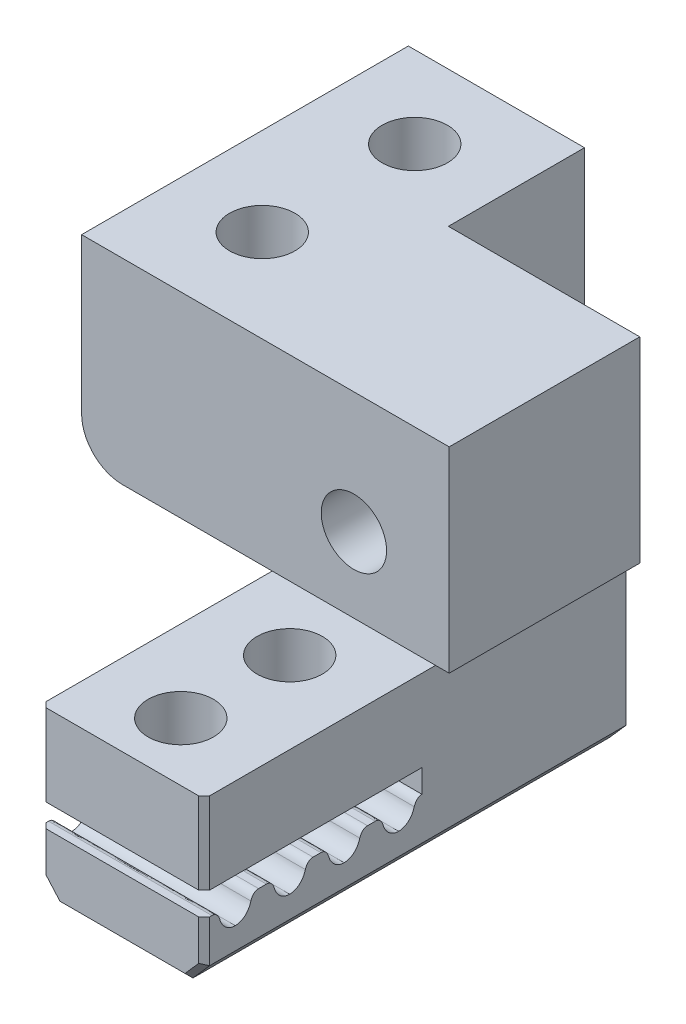
SolidWorks part; units mm, degrees
ref_plane "Front Plane" through (0, 0, 0) normal (0, 0, 1) x (1, 0, 0)
ref_plane "Top Plane" through (0, 0, 0) normal (0, 1, 0) x (1, 0, 0)
ref_plane "Right Plane" through (0, 0, 0) normal (1, 0, 0) x (0, 0, -1)
sketch "Sketch1" plane through (0, 0, 0) normal (0, 0, 1) x (1, 0, 0)
  line L0 (3, 3.05) -> (3, -2.2538)
  line L1 (-3, 3.05) -> (-3, -2.2538)
  line L7 (-3, 3.05) -> (3, 3.05)
  line L13 (-3, -2.2538) -> (-2.3882, -2.95)
  line L14 (3, -2.2538) -> (2.3882, -2.95)
  line L16 (-2.3882, -2.95) -> (2.3882, -2.95)
extrude "Boss-Extrude1" add sketch "Sketch1" along normal blind 13
sketch "Sketch6" plane through (0, 3.05, 0) normal (0, 1, 0) x (1, 0, 0)
  line L0 (-3, -5) -> (-3, 0)
  line L1 (-3, 0) -> (3, 0)
  line L3 (-3, -5) -> (3, -5)
  line L6 (3, -5) -> (3, 0)
  line L7 (3, 0) -> (-3, 0) construction
extrude "Boss-Extrude4" add sketch "Sketch6" along normal blind 5.6
sketch "Sketch16" plane through (0, 3.05, 0) normal (0, 1, 0) x (1, 0, 0)
  line L4 (3, -5) -> (-3, -5)
  line L5 (-3, -5) -> (-3, -13)
  line L6 (-3, -13) -> (3, -13)
  line L7 (3, -13) -> (3, -5)
  line L8 (3, -5) -> (-3, -5)
  line L9 (-3, -5) -> (-3, -13)
  line L10 (-3, -13) -> (3, -13)
  line L11 (3, -13) -> (3, -5)
  dimension "D1" = 0
extrude "Boss-Extrude5" add sketch "Sketch16" along normal blind 0.1
sketch "Sketch18" plane through (0, 0, 0) normal (1, 0, 0) x (0, 0, -1)
  line L0 (-8.8572, -0.0702) -> (-12.8572, -0.0702)
  line L2 (-12.8572, -0.7) -> (-12.7144, -0.7)
  line L3 (-11, -0.7) -> (-10.8572, -0.7)
  line L4 (-10.8572, -0.7) -> (-10.7144, -0.7)
  line L5 (-9, -0.7) -> (-8.8572, -0.7)
  line L6 (-8.8572, -0.7) -> (-8.7144, -0.7)
  line L7 (-7, -0.7) -> (-6.8572, -0.7)
  line L8 (-6.8572, -0.7) -> (-6.7144, -0.7)
  line L9 (-5, -0.0702) -> (-5, -0.7)
  line L11 (-5, -0.0702) -> (-8.8572, -0.0702)
  line L12 (-13, -2.95) -> (0, -2.95) construction
  line L13 (-5.8572, -1.45) -> (-5, -1.45) construction
  line L14 (-5, -1.45) -> (-11.8572, -1.45) construction
  line L15 (-5, 3.15) -> (-5, -1.45) construction
  line L16 (-5, -0.7) -> (-5, -1.45) construction
  line L17 (-12.8572, -0.0702) -> (-13, -0.0702)
  line L20 (-13, -0.0702) -> (-13, -0.7)
  line L22 (-12.8572, -0.7) -> (-13, -0.7)
  spline S0 degree 2 poles (-12.7144, -0.7) (-12.5198, -0.7) (-12.43, -0.9509) knots 0.103448 0.103448 0.103448 0.137931 0.137931 0.137931
  spline S1 degree 3 poles (-12.43, -0.9509) (-12.3594, -1.2388) (-12.13, -1.45) (-11.8572, -1.45) knots 0.137931 0.137931 0.137931 0.137931 0.172414 0.172414 0.172414 0.172414
  spline S2 degree 3 poles (-11.8572, -1.45) (-11.5844, -1.45) (-11.355, -1.2388) (-11.2844, -0.9509) knots 0.172414 0.172414 0.172414 0.172414 0.206897 0.206897 0.206897 0.206897
  spline S3 degree 2 poles (-11.2844, -0.9509) (-11.1946, -0.7) (-11, -0.7) knots 0.206897 0.206897 0.206897 0.241379 0.241379 0.241379
  spline S4 degree 2 poles (-10.7144, -0.7) (-10.5198, -0.7) (-10.43, -0.9509) knots 0.310345 0.310345 0.310345 0.344828 0.344828 0.344828
  spline S5 degree 3 poles (-10.43, -0.9509) (-10.3594, -1.2388) (-10.13, -1.45) (-9.8572, -1.45) knots 0.344828 0.344828 0.344828 0.344828 0.37931 0.37931 0.37931 0.37931
  spline S6 degree 3 poles (-9.8572, -1.45) (-9.5844, -1.45) (-9.355, -1.2388) (-9.2844, -0.9509) knots 0.37931 0.37931 0.37931 0.37931 0.413793 0.413793 0.413793 0.413793
  spline S7 degree 2 poles (-9.2844, -0.9509) (-9.1946, -0.7) (-9, -0.7) knots 0.413793 0.413793 0.413793 0.448276 0.448276 0.448276
  spline S8 degree 2 poles (-8.7144, -0.7) (-8.5198, -0.7) (-8.43, -0.9509) knots 0.517241 0.517241 0.517241 0.551724 0.551724 0.551724
  spline S9 degree 3 poles (-8.43, -0.9509) (-8.3594, -1.2388) (-8.13, -1.45) (-7.8572, -1.45) knots 0.551724 0.551724 0.551724 0.551724 0.586207 0.586207 0.586207 0.586207
  spline S10 degree 3 poles (-7.8572, -1.45) (-7.5844, -1.45) (-7.355, -1.2388) (-7.2844, -0.9509) knots 0.586207 0.586207 0.586207 0.586207 0.62069 0.62069 0.62069 0.62069
  spline S11 degree 2 poles (-7.2844, -0.9509) (-7.1946, -0.7) (-7, -0.7) knots 0.62069 0.62069 0.62069 0.655172 0.655172 0.655172
  spline S12 degree 2 poles (-6.7144, -0.7) (-6.5198, -0.7) (-6.43, -0.9509) knots 0.724138 0.724138 0.724138 0.758621 0.758621 0.758621
  spline S13 degree 3 poles (-6.43, -0.9509) (-6.3594, -1.2388) (-6.13, -1.45) (-5.8572, -1.45) knots 0.758621 0.758621 0.758621 0.758621 0.793103 0.793103 0.793103 0.793103
  spline S14 degree 3 poles (-5.8572, -1.45) (-5.5844, -1.45) (-5.355, -1.2388) (-5.2844, -0.9509) knots 0.793103 0.793103 0.793103 0.793103 0.827586 0.827586 0.827586 0.827586
  spline S15 degree 2 poles (-5.2844, -0.9509) (-5.1946, -0.7) (-5, -0.7) knots 0.827586 0.827586 0.827586 0.862069 0.862069 0.862069
  dimension "D1" = 1.5
  dimension "D2" = 1.3798
extrude "Cut-Extrude6" cut sketch "Sketch18" against normal blind 3.6 and the other way blind 4
sketch "Sketch15" plane through (0, 8.65, 0) normal (0, 1, 0) x (1, 0, 0)
  line L0 (0, -13) -> (0, -5) construction
  line L1 (-3, -13) -> (3, -13) construction
  line L2 (-3, -5) -> (3, -5) construction
  line L3 (2.008, -10.7144) -> (2.008, -11) construction
  line L4 (3, -10.7144) -> (-3, -10.7144) construction
  line L5 (3, -11) -> (-3, -11) construction
  line L6 (2.008, -10.8572) -> (0, -10.8572) construction
  line L7 (1.0382, -6.7144) -> (1.0382, -7) construction
  line L8 (3, -6.7144) -> (-3, -6.7144) construction
  line L9 (3, -7) -> (-3, -7) construction
  line L10 (1.0382, -6.8572) -> (0, -6.8572) construction
  circle A0 centre (0, -6.8572) radius 1.5 construction
  circle A1 centre (0, -10.8572) radius 1.5 construction
  circle A2 centre (0, -10.8572) radius 1.2
  circle A4 centre (0, -6.8572) radius 1.2
extrude "Cut-Extrude7" cut sketch "Sketch15" against normal up to surface (8.7202 mm away) up to face at (0, -0.0702, 9)
sketch "Sketch19" plane through (0, -0.0702, 0) normal (0, -1, 0) x (1, 0, 0)
  line L4 (-3, 13) -> (-3, 5)
  line L5 (-3, 5) -> (3, 5)
  line L6 (3, 5) -> (3, 13)
  line L7 (3, 13) -> (-3, 13)
  line L8 (-3, 13) -> (-3, 5)
  line L9 (-3, 5) -> (3, 5)
  line L10 (3, 5) -> (3, 13)
  line L11 (3, 13) -> (-3, 13)
  circle A0 centre (0, 10.8572) radius 1.2 construction
  circle A1 centre (0, 6.8572) radius 1.2 construction
  circle A2 centre (0, 10.8572) radius 1.2
  circle A3 centre (0, 6.8572) radius 1.2
  dimension "D1" = 0
extrude "Cut-Extrude8" cut sketch "Sketch19" against normal blind 0.2202
sketch "Sketch12" plane through (0, 0, 5) normal (0, 0, 1) x (1, 0, 0)
  circle A0 centre (0, 5.85) radius 1.5 construction
  circle A1 centre (0, 5.85) radius 1.2
extrude "Cut-Extrude5" cut sketch "Sketch12" against normal blind 6
sketch "Sketch21" plane through (0, 0, 0) normal (0, 0, -1) x (-1, 0, 0)
  line L10 (-2.3882, -2.95) -> (2.3882, -2.95)
  line L11 (2.3882, -2.95) -> (3, -2.2538)
  line L12 (3, -2.2538) -> (3, 8.65)
  line L13 (3, 8.65) -> (-3, 8.65)
  line L14 (-3, 8.65) -> (-3, -2.2538)
  line L15 (-3, -2.2538) -> (-2.3882, -2.95)
  line L19 (-2.3882, -2.95) -> (2.3882, -2.95)
  line L20 (2.3882, -2.95) -> (3, -2.2538)
  line L21 (3, -2.2538) -> (3, 8.65)
  line L22 (3, 8.65) -> (-3, 8.65)
  line L23 (-3, 8.65) -> (-3, -2.2538)
  line L24 (-3, -2.2538) -> (-2.3882, -2.95)
  circle A0 centre (0, 5.85) radius 1.2 construction
  circle A1 centre (0, 5.85) radius 1.2
  dimension "D1" = 0
extrude "Boss-Extrude6" add sketch "Sketch21" along normal blind 2.5
sketch "Sketch24" plane through (0, 0, 5) normal (0, 0, 1) x (1, 0, 0)
  line L4 (-3, 8.65) -> (-3, 3.15)
  line L5 (-3, 3.15) -> (3, 3.15)
  line L6 (3, 3.15) -> (3, 8.65)
  line L7 (3, 8.65) -> (-3, 8.65)
  line L8 (-3, 8.65) -> (-3, 3.15)
  line L9 (-3, 3.15) -> (3, 3.15)
  line L10 (3, 3.15) -> (3, 8.65)
  line L11 (3, 8.65) -> (-3, 8.65)
  dimension "D1" = 0
extrude "Cut-Extrude10" cut sketch "Sketch24" against normal blind 8.5
sketch "Sketch25" plane through (0, 3.15, 0) normal (0, 1, 0) x (1, 0, 0)
  line L2 (0, -4.5) -> (3.5, -4.5)
  line L3 (3.5, 2.5) -> (-10, 2.5)
  line L5 (0, -4.5) -> (-10, -4.5)
  line L6 (-10, 2.5) -> (-10, -4.5)
  line L8 (3.5, 2.5) -> (3.5, -4.5)
  dimension "D1" = 7
extrude "Boss-Extrude8" add sketch "Sketch25" along normal blind 7.2
fillet "Fillet4" radius 1.5 1 edges at (-10, 3.15, 1)
sketch "Sketch26" plane through (0, 0, 4.5) normal (0, 0, 1) x (1, 0, 0)
  circle A0 centre (0, 5.9) radius 1.5 construction
  circle A1 centre (0, 5.9) radius 1.5 construction
  circle A2 centre (0, 5.9) radius 1.2
extrude "Cut-Extrude11" cut sketch "Sketch26" against normal blind 10
chamfer "Chamfer1" distance 0.2 angle 45 7 edges at (-3, 1.65, 13) (-3, -1.4769, 13) (-2.6941, -2.6019, 13) (0, -2.95, 13) (2.6941, -2.6019, 13) (3, -1.4769, 13) (3, 1.65, 13)
sketch "Sketch29" plane through (0, 0, -2.5) normal (0, 0, -1) x (-1, 0, 0)
  line L2 (3.53, 3.15) -> (3.53, 10.35)
  line L13 (3, 3.15) -> (8.5, 3.15)
  line L14 (10, 4.65) -> (10, 10.35)
  line L15 (10, 10.35) -> (-3.5, 10.35)
  line L16 (-3.5, 10.35) -> (-3.5, 3.15)
  line L17 (-3.5, 3.15) -> (-3, 3.15)
  line L18 (-3, 3.15) -> (-3, -2.2538)
  line L19 (-3, -2.2538) -> (-2.3882, -2.95)
  line L20 (-2.3882, -2.95) -> (2.3882, -2.95)
  line L24 (2.3882, -2.95) -> (3, -2.2538)
  line L25 (3, -2.2538) -> (3, 3.15)
  line L26 (3.53, 3.15) -> (8.5, 3.15)
  line L27 (10, 4.65) -> (10, 10.35)
  line L28 (10, 10.35) -> (3.53, 10.35)
  arc A2 (8.5, 3.15) -> (10, 4.65) centre (8.5, 4.65) ccw
  arc A4 (8.5, 3.15) -> (10, 4.65) centre (8.5, 4.65) ccw
  dimension "D1" = 0
extrude "Boss-Extrude9" add sketch "Sketch29" along normal blind 5
sketch "Sketch31" plane through (0, 10.35, 0) normal (0, 1, 0) x (1, 0, 0)
  line L0 (-6.765, 7.5) -> (-6.765, 1.5) construction
  line L1 (-10, 7.5) -> (-3.53, 7.5) construction
  line L3 (-0.015, 2.5) -> (0, -4.5) construction
  line L5 (-6.765, 1.5) -> (-4.5254, 1.5) construction
  line L7 (-3.53, -1.1) -> (-10, -1.1) construction
  line L8 (-10, 7.5) -> (-10, -4.5) construction
  line L9 (3.5, 2.5) -> (-3.53, 2.5) construction
  line L10 (-3, -4.5) -> (3, -4.5) construction
  line L11 (-10, -4.5) -> (3.5, -4.5) construction
  circle A0 centre (-6.765, 4.5) radius 1.2
  circle A1 centre (-6.765, -1.1) radius 1.2
  circle A2 centre (-6.765, -1.1) radius 2.75 construction
  circle A3 centre (-6.765, 4.5) radius 2.75 construction
  dimension "D1" = 2.4
  dimension "D2" = 3.4
  dimension "D3" = 3
extrude "Cut-Extrude12" cut sketch "Sketch31" against normal blind 8
